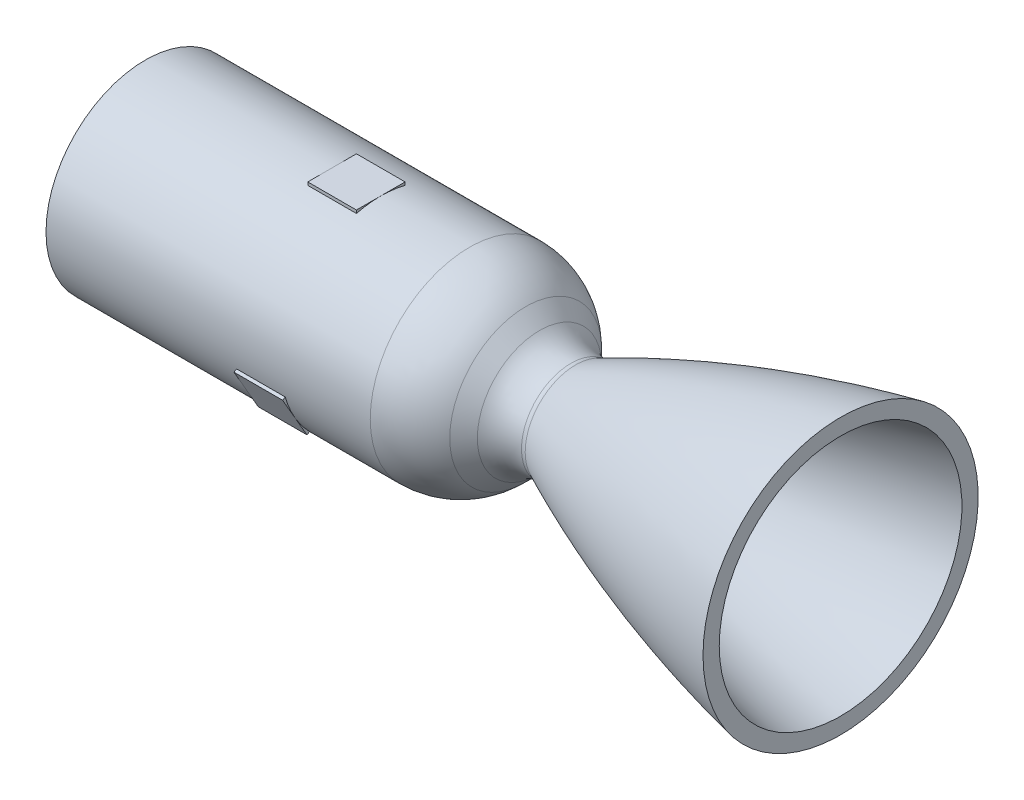
SolidWorks part; units mm, degrees
material "Inconel 718"
ref_plane "Front Plane" through (0, 0, 0) normal (0, 0, 1) x (1, 0, 0)
ref_plane "Top Plane" through (0, 0, 0) normal (0, 1, 0) x (1, 0, 0)
ref_plane "Right Plane" through (0, 0, 0) normal (1, 0, 0) x (0, 0, -1)
sketch "Sketch1" plane through (0, 0, 0) normal (0, 0, 1) x (1, 0, 0)
  line L0 (-14.1241, 4.5946) -> (-19.5266, 9.9971)
  line L1 (-168.4473, 19.1127) -> (-41.5336, 19.1127)
  line L2 (-168.4473, -13.3985) -> (103.7057, -13.3985) construction
  line L3 (-14.1241, 10.9446) -> (-19.5266, 16.3471)
  line L4 (-168.4473, 25.4627) -> (-41.5336, 25.4627)
  line L5 (-168.4473, 25.4627) -> (-168.4473, 19.1127)
  line L6 (103.7057, 34.1014) -> (103.7057, 40.4514) construction
  line L7 (103.7057, 34.1014) -> (103.7057, 40.4514)
  arc A0 (0, 0) -> (-1.8625, -0.4129) centre (-1.8625, 3.9941) cw
  arc A1 (-1.8625, -0.4129) -> (-14.1241, 4.5946) centre (-1.9488, 16.8919) cw
  arc A2 (-41.5336, 19.1127) -> (-19.5266, 9.9971) centre (-41.5336, -12.0099) cw
  arc A3 (0, 6.35) -> (-1.8625, 5.9371) centre (-1.8625, 10.3441) cw
  arc A4 (-1.8625, 5.9371) -> (-14.1241, 10.9446) centre (-1.9488, 23.2419) cw
  arc A5 (-41.5336, 25.4627) -> (-19.5266, 16.3471) centre (-41.5336, -5.6599) cw
  spline S0 degree 6 poles (-9.851, -4.7434) (10.8035, 5.5214) (31.4581, 14.1551) (52.1126, 21.3892) (72.7671, 27.3863) (93.4217, 32.2746) (114.0762, 36.1581) knots 0 0 0 0 0 0 0 1 1 1 1 1 1 1 construction
  spline S1 degree 6 poles (0, 0) (17.2843, 8.0593) (34.5686, 15.0262) (51.8528, 21.027) (69.1371, 26.157) (86.4214, 30.4936) (103.7057, 34.1014) knots 0.07949 0.07949 0.07949 0.07949 0.07949 0.07949 0.07949 0.916317 0.916317 0.916317 0.916317 0.916317 0.916317 0.916317
  spline S2 degree 6 poles (-9.851, 1.6066) (10.8035, 11.8714) (31.4581, 20.5051) (52.1126, 27.7392) (72.7671, 33.7363) (93.4217, 38.6246) (114.0762, 42.5081) knots 0 0 0 0 0 0 0 1 1 1 1 1 1 1 construction
  spline S3 degree 6 poles (0, 6.35) (17.2843, 14.4093) (34.5686, 21.3762) (51.8528, 27.377) (69.1371, 32.507) (86.4214, 36.8436) (103.7057, 40.4514) knots 0.07949 0.07949 0.07949 0.07949 0.07949 0.07949 0.07949 0.916317 0.916317 0.916317 0.916317 0.916317 0.916317 0.916317
revolve "Revolve1" add sketch "Sketch1" angle 360 about L2
ref_plane "Plane1" through (0, 25.4627, 0) normal (0, 1, 0) x (1, 0, 0)
sketch "Sketch2" plane through (0, 25.4627, 0) normal (0, 1, 0) x (1, 0, 0)
  line L0 (-168.4473, 0) -> (-41.5336, 0) construction
  line L1 (-76.2743, 9.525) -> (-95.3243, 9.525)
  line L2 (-76.2743, 9.525) -> (-76.2743, -9.525)
  line L3 (-76.2743, -9.525) -> (-95.3243, -9.525)
  line L4 (-95.3243, 9.525) -> (-95.3243, -9.525)
  line L5 (-76.2743, 9.525) -> (-95.3243, -9.525) construction
  line L6 (-76.2743, -9.525) -> (-95.3243, 9.525) construction
  point P0 (-85.7993, 0)
  dimension "D1" = 19.05
  dimension "D2" = 19.05
extrude "Boss-Extrude1" add sketch "Sketch2" against normal up to next
pattern_circular "CirPattern1" count 3 over 360 about axis through (0, -13.3985, 0) along (1, 0, 0) of "Boss-Extrude1"
